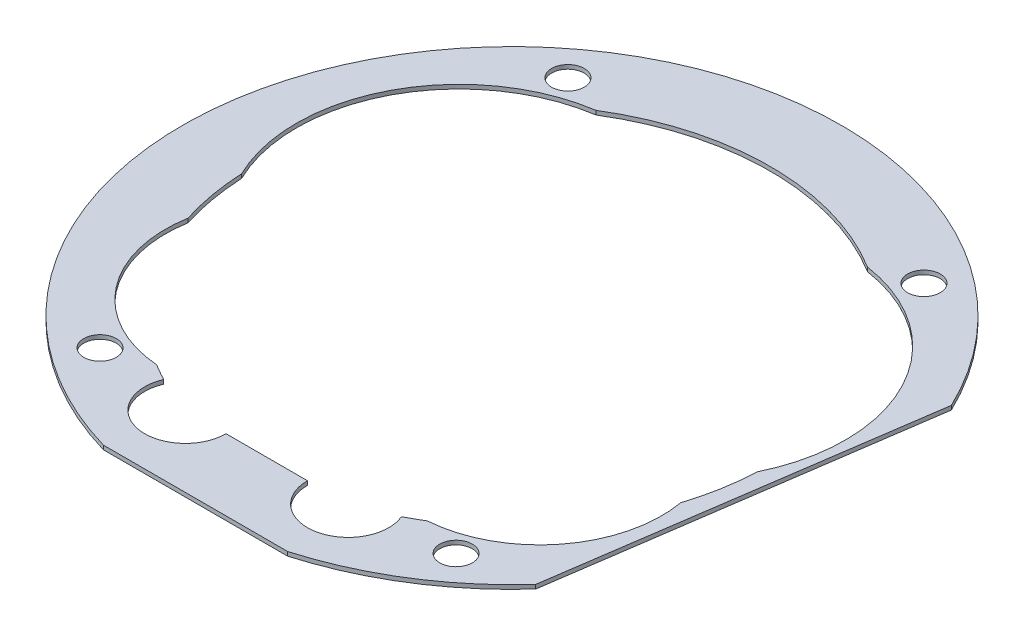
SolidWorks part; units mm, degrees
ref_plane "Front Plane" through (0, 0, 0) normal (0, 0, 1) x (1, 0, 0)
ref_plane "Top Plane" through (0, 0, 0) normal (0, 1, 0) x (1, 0, 0)
ref_plane "Right Plane" through (0, 0, 0) normal (1, 0, 0) x (0, 0, -1)
sketch "Sketch1" plane through (0, 0, 0) normal (0, 1, 0) x (1, 0, 0)
  line L1 (-4, -24.1073) -> (4, -24.1073)
  line L2 (29.2378, 13.961) -> (24.0491, -21.7118)
  line L3 (-9.0608, -31.1073) -> (9.0608, -31.1073)
  arc A0 (11.6854, -22.5524) -> (13.2979, -21.6409) centre (0, 0) ccw
  circle A1 centre (-17.5, 23) radius 1.6
  arc A2 (9.0608, -31.1073) -> (24.0491, -21.7118) centre (0, 0) ccw
  arc A3 (29.2378, 13.961) -> (-9.0608, -31.1073) centre (0, 0) ccw
  circle A4 centre (-17.5, -23) radius 1.6
  circle A5 centre (17.5, -23) radius 1.6
  circle A6 centre (17.5, 23) radius 1.6
  arc A7 (-4, -24.1073) -> (-11.6854, -22.5524) centre (-8, -24.1073) cw
  arc A8 (4, -24.1073) -> (11.6854, -22.5524) centre (8, -24.1073) ccw
  arc A9 (-25.3711, -1.2112) -> (-13.348, 21.61) centre (-10.9822, 5.7858) cw
  arc A10 (13.348, 21.61) -> (25.3711, -1.2112) centre (10.9822, 5.7858) cw
  arc A11 (-25.3711, -1.2112) -> (-24.2253, -7.6352) centre (0, 0) ccw
  arc A12 (13.348, 21.61) -> (-13.348, 21.61) centre (0, 0) ccw
  arc A13 (-24.2253, -7.6352) -> (-13.2979, -21.6409) centre (-12.3998, -9.6745) ccw
  arc A14 (13.2979, -21.6409) -> (24.2253, -7.6352) centre (12.3998, -9.6745) ccw
  arc A15 (-13.2979, -21.6409) -> (-11.6854, -22.5524) centre (0, 0) ccw
  arc A16 (24.2253, -7.6352) -> (25.3711, -1.2112) centre (0, 0) ccw
  point P33 (-14.66, 20.7423)
  point P34 (-13.2979, 21.61)
  dimension "D1" = 3.2
  dimension "D2" = 3.2
  dimension "D3" = 3.2
  dimension "D4" = 3.2
  dimension "D10" = 7
  dimension "D11" = 25.4
  dimension "D12" = 32.4
  dimension "D15" = 4
  dimension "D16" = 4
  dimension "D20" = 30
  dimension "D21" = 16
  dimension "D22" = 16
  dimension "D24" = 12
  dimension "D26" = 12
  dimension "D27" = 20
  dimension "D5" = 17.5
  dimension "D6" = 23
  dimension "D7" = 46
  dimension "D8" = 35
  dimension "D9" = 7
  dimension "D13" = 16
  dimension "D14" = 36.0481
  dimension "D17" = 8
  dimension "D18" = 7.8411
  dimension "D19" = 7.8411
  dimension "D23" = 30
  dimension "D25" = 20
extrude "Boss-Extrude1" add sketch "Sketch1" along normal blind 0.4
